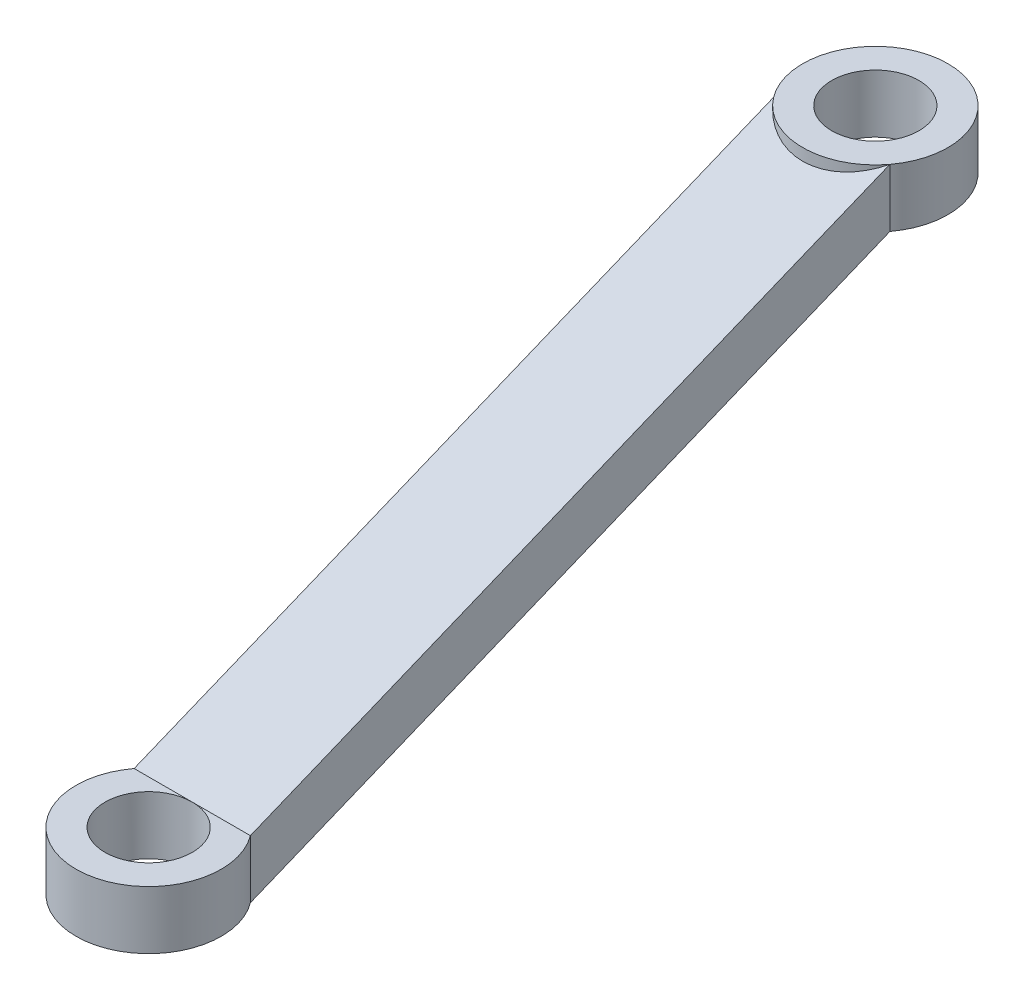
SolidWorks part; units mm, degrees
ref_plane "Front Plane" through (0, 0, 0) normal (0, 0, 1) x (1, 0, 0)
ref_plane "Top Plane" through (0, 0, 0) normal (0, 1, 0) x (1, 0, 0)
ref_plane "Right Plane" through (0, 0, 0) normal (1, 0, 0) x (0, 0, -1)
sketch "Sketch1" plane through (0, 0, 0) normal (1, 0, 0) x (0, 0, -1)
  line L0 (59.7041, 0) -> (-56.2867, 0) construction
  line L1 (0, 39.8696) -> (0, -65.0649) construction
  line L2 (0, 0) -> (0, 2)
  line L3 (0, 2) -> (22, 11)
  line L4 (22, 11) -> (22, 9)
  line L5 (22, 9) -> (0, 0)
  dimension "D1" = 22
  dimension "D2" = 11
  dimension "D3" = 2
extrude "Boss-Extrude1" add sketch "Sketch1" along normal blind 4
sketch "Sketch2" plane through (0, 0, 0) normal (0, 1, 0) x (1, 0, 0)
  circle A0 centre (2, -1.5) radius 2.5
  dimension "D1" = 5
extrude "Boss-Extrude2" add sketch "Sketch2" along normal up to vertex (2 mm away) up to point (4, 2, 0)
ref_plane "Plane1" through (0, 9, 0) normal (0, -1, 0) x (-1, 0, 0)
sketch "Sketch3" plane through (0, 9, 0) normal (0, -1, 0) x (-1, 0, 0)
  circle A0 centre (-2, 23.5) radius 2.5
  dimension "D1" = 5
extrude "Boss-Extrude3" add sketch "Sketch3" against normal up to vertex (2 mm away)
sketch "Sketch4" plane through (0, 2, 0) normal (0, 1, 0) x (1, 0, 0)
  circle A0 centre (2, -1.5) radius 2.5 construction
  circle A1 centre (2, -1.5) radius 1.5
  dimension "D1" = 3
extrude "Cut-Extrude1" cut sketch "Sketch4" against normal through all
sketch "Sketch5" plane through (0, 11, 0) normal (0, 1, 0) x (1, 0, 0)
  circle A0 centre (2, 23.5) radius 2.5 construction
  circle A1 centre (2, 23.5) radius 1.5
  dimension "D1" = 3
extrude "Cut-Extrude2" cut sketch "Sketch5" against normal through all
